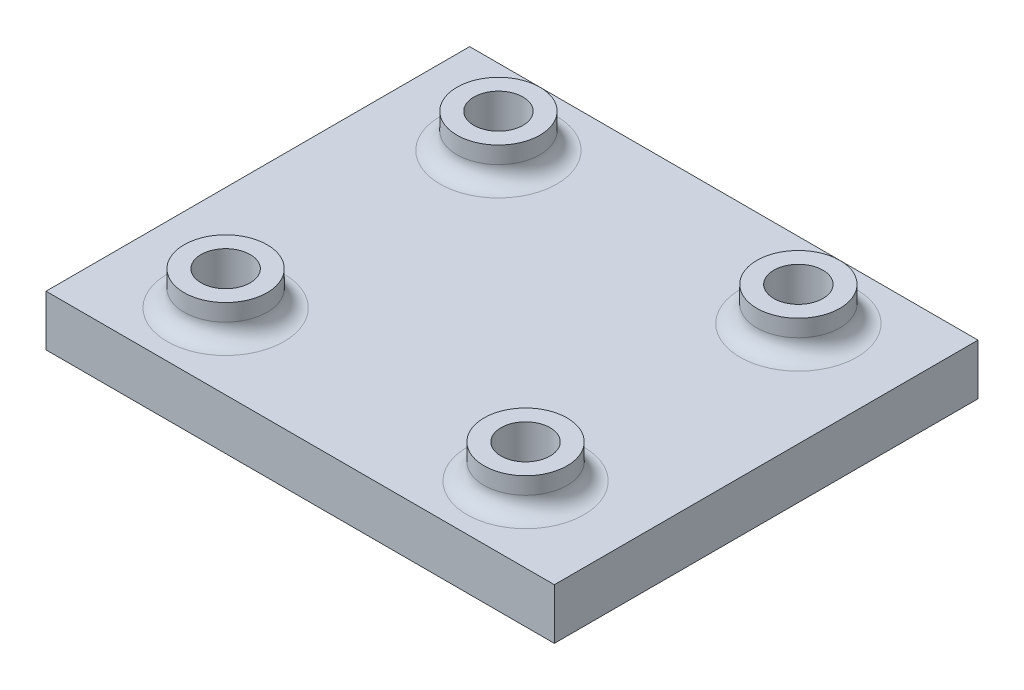
SolidWorks part; units mm, degrees
ref_plane "Front Plane" through (0, 0, 0) normal (0, 0, 1) x (1, 0, 0)
ref_plane "Top Plane" through (0, 0, 0) normal (0, 1, 0) x (1, 0, 0)
ref_plane "Right Plane" through (0, 0, 0) normal (1, 0, 0) x (0, 0, -1)
sketch "Sketch1" plane through (0, 0, 0) normal (0, 1, 0) x (1, 0, 0)
  line L0 (15, 25) -> (15, 0) construction
  line L1 (0, 0) -> (30, 0)
  line L2 (0, 0) -> (0, 25)
  line L3 (0, 25) -> (30, 25)
  line L4 (30, 0) -> (30, 25)
  line L5 (0, 12.5) -> (30, 12.5) construction
  circle A0 centre (6.15, 20.55) radius 1.45
  circle A1 centre (23.85, 20.55) radius 1.45
  circle A2 centre (6.15, 4.45) radius 1.45
  circle A3 centre (23.85, 4.45) radius 1.45
  dimension "D3" = 2.9
  dimension "D1" = 30
  dimension "D2" = 25
  dimension "D4" = 17.7
  dimension "D5" = 16.1
extrude "Boss-Extrude1" add sketch "Sketch1" along normal blind 3
sketch "Sketch2" plane through (0, 3, 0) normal (0, 1, 0) x (1, 0, 0)
  circle A0 centre (6.15, 20.55) radius 1.45
  circle A1 centre (6.15, 20.55) radius 2.45
  circle A2 centre (6.15, 20.55) radius 1.45 construction
  circle A3 centre (23.85, 20.55) radius 1.45
  circle A4 centre (23.85, 20.55) radius 2.45
  circle A5 centre (6.15, 4.45) radius 1.45
  circle A6 centre (6.15, 4.45) radius 2.45
  circle A7 centre (23.85, 4.45) radius 1.45
  circle A8 centre (23.85, 4.45) radius 2.45
  circle A9 centre (23.85, 20.55) radius 1.45 construction
  dimension "D1" = 1
extrude "Boss-Extrude2" add sketch "Sketch2" along normal blind 2
sketch "Sketch3" plane through (0, 0, 0) normal (0, -1, 0) x (1, 0, 0)
  line L0 (30, -25) -> (0, -25) construction
  line L1 (7.68, -7.1) -> (9.21, -4.45)
  line L2 (9.21, -4.45) -> (7.68, -1.8)
  line L3 (7.68, -1.8) -> (4.62, -1.8)
  line L4 (4.62, -1.8) -> (3.09, -4.45)
  line L5 (3.09, -4.45) -> (4.62, -7.1)
  line L6 (4.62, -7.1) -> (7.68, -7.1)
  line L7 (25.38, -7.1) -> (26.91, -4.45)
  line L8 (26.91, -4.45) -> (25.38, -1.8)
  line L9 (25.38, -1.8) -> (22.32, -1.8)
  line L10 (22.32, -1.8) -> (20.79, -4.45)
  line L11 (20.79, -4.45) -> (22.32, -7.1)
  line L12 (22.32, -7.1) -> (25.38, -7.1)
  line L13 (25.38, -23.2) -> (26.91, -20.55)
  line L14 (26.91, -20.55) -> (25.38, -17.9)
  line L15 (25.38, -17.9) -> (22.32, -17.9)
  line L16 (22.32, -17.9) -> (20.79, -20.55)
  line L17 (20.79, -20.55) -> (22.32, -23.2)
  line L18 (22.32, -23.2) -> (25.38, -23.2)
  line L19 (7.68, -23.2) -> (9.21, -20.55)
  line L20 (9.21, -20.55) -> (7.68, -17.9)
  line L21 (7.68, -17.9) -> (4.62, -17.9)
  line L22 (4.62, -17.9) -> (3.09, -20.55)
  line L23 (3.09, -20.55) -> (4.62, -23.2)
  line L24 (4.62, -23.2) -> (7.68, -23.2)
  circle A0 centre (6.15, -4.45) radius 2.65 construction
  circle A1 centre (23.85, -4.45) radius 2.65 construction
  circle A2 centre (23.85, -20.55) radius 2.65 construction
  circle A3 centre (6.15, -20.55) radius 2.65 construction
  dimension "D1" = 5.3
extrude "Cut-Extrude1" cut sketch "Sketch3" against normal blind 2
fillet "Fillet1" radius 1 4 edges at (6.15, 3, -23) (23.85, 3, -23) (23.85, 3, -6.9) (6.15, 3, -6.9)
